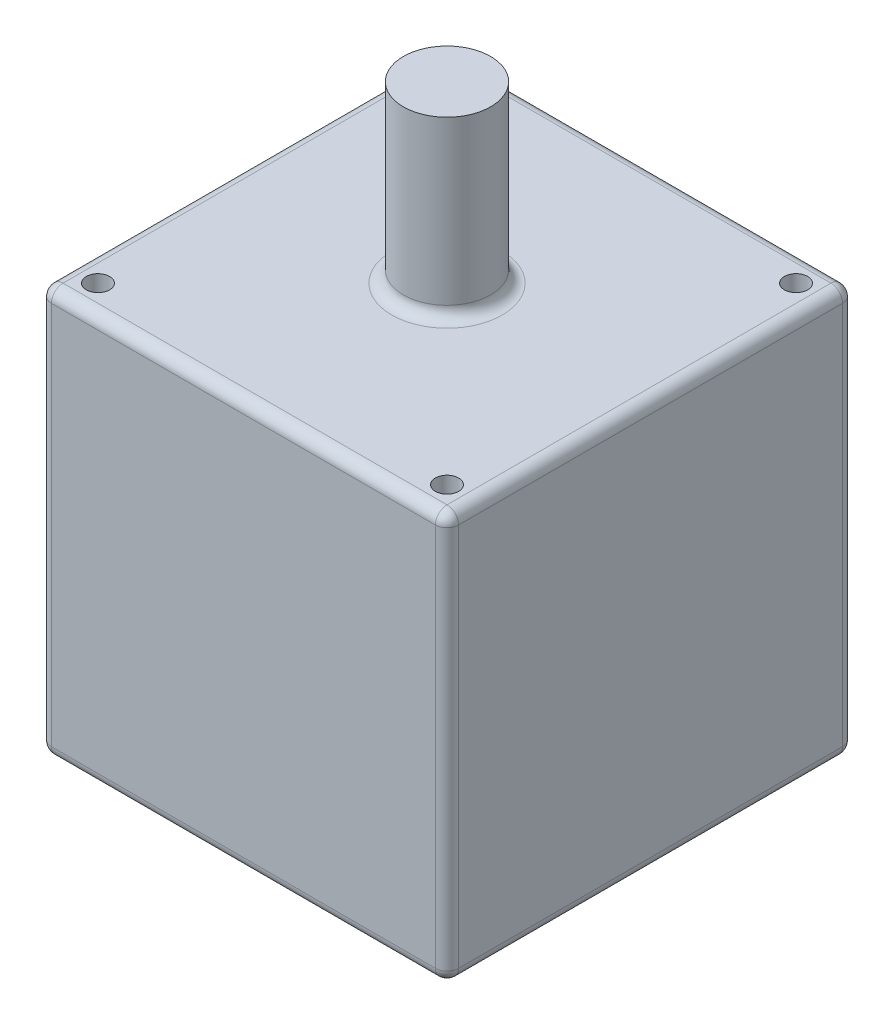
SolidWorks part; units mm, degrees
ref_plane "Front Plane" through (0, 0, 0) normal (0, 0, 1) x (1, 0, 0)
ref_plane "Top Plane" through (0, 0, 0) normal (0, 1, 0) x (1, 0, 0)
ref_plane "Right Plane" through (0, 0, 0) normal (1, 0, 0) x (0, 0, -1)
sketch "Sketch1" plane through (0, 0, 0) normal (0, 1, 0) x (1, 0, 0)
  line L1 (-17.5, 17.5) -> (17.5, 17.5)
  line L2 (-17.5, 17.5) -> (-17.5, -17.5)
  line L3 (-17.5, -17.5) -> (17.5, -17.5)
  line L4 (17.5, 17.5) -> (17.5, -17.5)
  line L5 (-17.5, 17.5) -> (17.5, -17.5) construction
  line L6 (-17.5, -17.5) -> (17.5, 17.5) construction
  point P1 (0, 0)
  dimension "D1" = 35
  dimension "D2" = 35
extrude "Boss-Extrude1" add sketch "Sketch1" along normal blind 35
sketch "Sketch2" plane through (0, 35, 0) normal (0, 1, 0) x (1, 0, 0)
  circle A0 centre (0, 0) radius 3.75
  dimension "D1" = 7.5
extrude "Boss-Extrude2" add sketch "Sketch2" along normal blind 15
fillet "Fillet1" radius 1 13 edges at (17.5, 17.5, -17.5) (-17.5, 17.5, -17.5) (-17.5, 17.5, 17.5) (17.5, 17.5, 17.5) (0, 35, 17.5) (-17.5, 35, 0) (0, 35, -17.5) (17.5, 35, 0) (0, 35, 3.75) (0, 0, -17.5) (-17.5, 0, 0) (0, 0, 17.5) (17.5, 0, 0)
sketch "Sketch3" plane through (0, 35, 0) normal (0, 1, 0) x (1, 0, 0)
  line L1 (-15, 15) -> (15, 15)
  line L2 (-15, 15) -> (-15, -15)
  line L3 (-15, -15) -> (15, -15)
  line L4 (15, 15) -> (15, -15)
  line L5 (-15, 15) -> (15, -15) construction
  line L6 (-15, -15) -> (15, 15) construction
  point P0 (0, 0)
  dimension "D1" = 30
  dimension "D2" = 30
hole_wizard "Ø2.0mm Dowel Hole1" positions "Sketch4" profile "Sketch5" hole size "Ø2.0" standard "ANSI Metric"
sketch "Sketch4" plane through (0, 35, 0) normal (0, 1, 0) x (1, 0, 0)
  point P0 (-15, 15)
  point P3 (15, 15)
  point P6 (15, -15)
  point P9 (-15, -15)
sketch "Sketch5" plane through (-15, 35, -15) normal (1, 0, 0) x (0, 0, 1)
  line L0 (0, 0) -> (0, 10.6009)
  line L1 (0, 10.6009) -> (1, 10)
  line L2 (1, 10) -> (1, 0)
  line L5 (1, 0) -> (0, 0)
  line L10 (0, 10.6009) -> (-1, 10) construction
  line L11 (0, -6.35) -> (0, 107.95) construction
  dimension "Hole Dia." = 2
  dimension "Hole Depth" = 10
  dimension "Drill Angle" = 118
